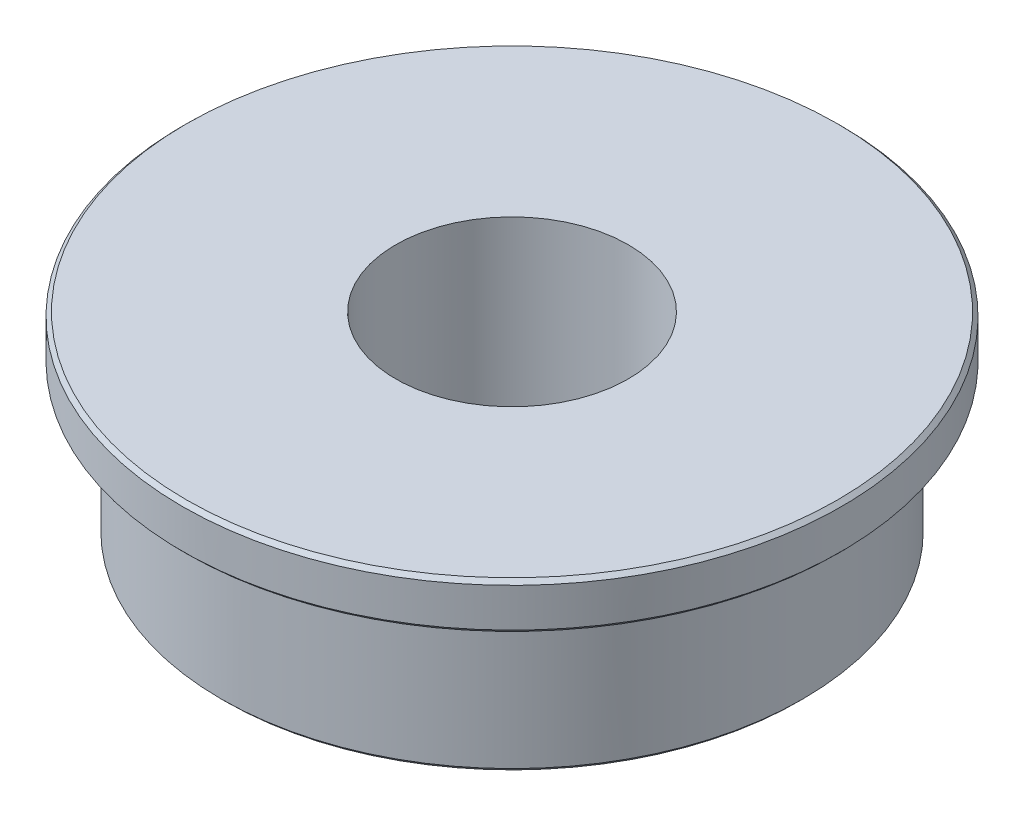
SolidWorks part; units mm, degrees
ref_plane "前视基准面" through (0, 0, 0) normal (0, 0, 1) x (1, 0, 0)
ref_plane "上视基准面" through (0, 0, 0) normal (0, 1, 0) x (1, 0, 0)
ref_plane "右视基准面" through (0, 0, 0) normal (1, 0, 0) x (0, 0, -1)
sketch "草图1" plane through (0, 0, 0) normal (0, 0, 1) x (1, 0, 0)
  line L0 (3, 0) -> (3, 5)
  line L1 (3, 5) -> (8.5, 5)
  line L2 (8.5, 5) -> (8.5, 3.8)
  line L3 (8.5, 3.8) -> (7.5, 3.8)
  line L4 (7.5, 3.8) -> (7.5, 0)
  line L5 (7.5, 0) -> (3, 0)
  line L6 (0, 0) -> (0, 5.9585) construction
  dimension "D1" = 3
  dimension "D2" = 8.5
  dimension "D3" = 7.5
  dimension "D4" = 5
  dimension "D5" = 1.2
revolve "旋转1" add sketch "草图1" angle 360 about L6
chamfer "倒角1" distance 0.1 angle 45 3 edges at (0, 0, -7.5) (0, 3.8, -8.5) (0, 5, -8.5)
